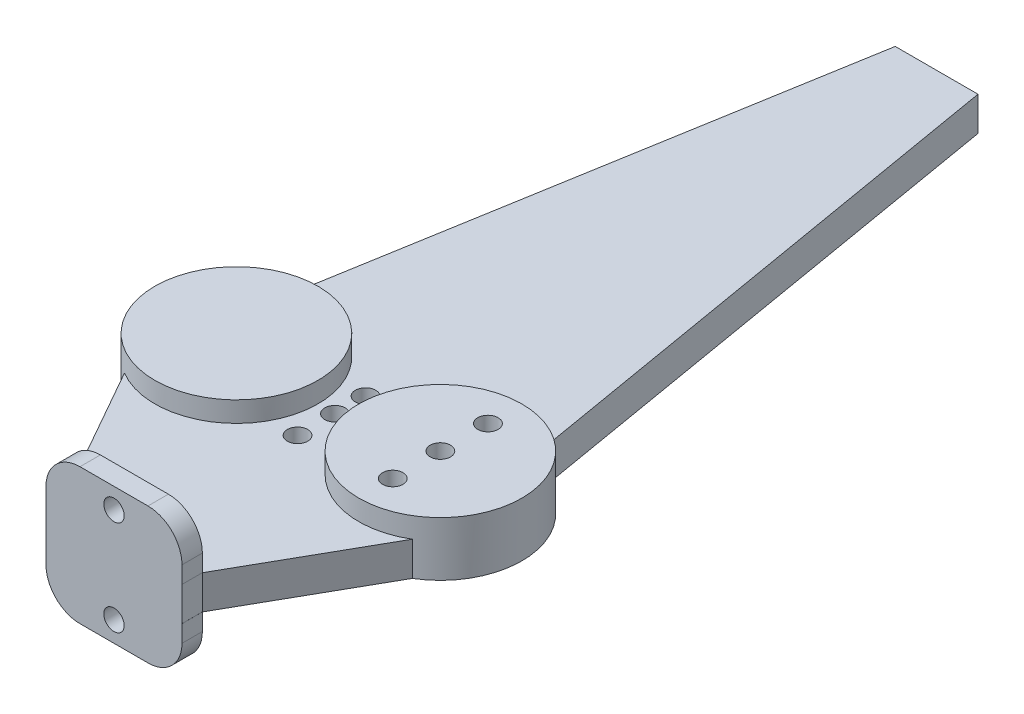
SolidWorks part; units mm, degrees
ref_plane "Front Plane" through (0, 0, 0) normal (0, 0, 1) x (1, 0, 0)
ref_plane "Top Plane" through (0, 0, 0) normal (0, 1, 0) x (1, 0, 0)
ref_plane "Right Plane" through (0, 0, 0) normal (1, 0, 0) x (0, 0, -1)
sketch "Sketch1" plane through (0, 0, 0) normal (0, 1, 0) x (1, 0, 0)
  line L0 (-10, -44) -> (10, -44)
  line L1 (-6.0865, 59) -> (6.0865, 59)
  line L3 (-10, -59) -> (10, -59)
  line L6 (-19.4049, -42.4032) -> (-18.521, -40.4718) construction
  line L7 (-10, -44) -> (-10, -59)
  line L8 (10, -44) -> (10, -59)
  line L9 (-10, -59) -> (10, -59)
  line L12 (0, 23.2923) -> (-7.3391, -19.7636)
  line L16 (-21.1665, -39.2944) -> (-10, -59)
  line L17 (-7.9884, -19.2616) -> (-7.7512, -16.9378) construction
  line L21 (0, 23.2923) -> (7.3391, -19.7636)
  line L22 (21.1665, -39.2944) -> (10, -59)
  line L23 (18.521, -40.4718) -> (19.4049, -42.4032) construction
  line L24 (6.0865, 59) -> (19.1685, -17.7473)
  line L25 (-8.6201, -18.8365) -> (-6.3269, -13.8254) construction
  line L26 (6.3269, -13.8254) -> (8.6201, -18.8365) construction
  line L28 (7.7512, -16.9378) -> (7.9884, -19.2616) construction
  line L29 (-6.0865, 59) -> (-19.1685, -17.7473)
  circle A0 centre (15, -29) radius 12
  circle A1 centre (-15, -29) radius 12
  point P0 (0, 0)
  point P6 (-15, -29)
  point P7 (0, -51.5)
  point P8 (15, -29)
  point P16 (0, 59)
  point P17 (0, 59)
  dimension "D3" = 20
  dimension "D4" = 15
  dimension "D5" = 30
  dimension "D6" = 30
extrude "Boss-Extrude1" add sketch "Sketch1" along normal blind 5 contours A1 L12 L21 A0 L24 L1 L29 | A1 L16 L7 L0 L8 L22 A0 L21 L12 | A0 | A1 | L8 L0 L7 L3
sketch "Sketch2" plane through (0, 5, 0) normal (0, 1, 0) x (1, 0, 0)
  circle A0 centre (15, -29) radius 12
  circle A1 centre (-15, -29) radius 12
extrude "Boss-Extrude2" add sketch "Sketch2" along normal blind 3
sketch "Sketch3" plane through (0, 0, 59) normal (0, 0, 1) x (1, 0, 0)
  line L0 (-10, 5) -> (-10, 0)
  line L6 (-10.0072, 12.5) -> (9.9928, 12.5)
  line L9 (9.9855, 5) -> (9.9855, 0)
  line L10 (-10, 5) -> (-10, 0) construction
  line L13 (-10.0072, 12.5) -> (-10.0072, -7.5)
  line L14 (-10.0072, -7.5) -> (9.9928, -7.5)
  line L15 (9.9928, 12.5) -> (9.9928, -7.5)
  point P0 (-0.0072, 2.5)
  point P13 (-0.0072, 5)
  point P14 (9.9855, 2.5)
  point P15 (-0.0072, 2.5)
  point P17 (-0.0072, 2.5)
  line M9 (-10, 0) -> (10, 0)
  line M11 (10, 5) -> (-10, 5)
  line M12 (-10, 5) -> (-10, 0)
  dimension "D1" = 20
  dimension "D2" = 20
  dimension "D4" = 9.9928
extrude "Boss-Extrude12" add sketch "Sketch3" along normal blind 3 separate body contours L15 L6 L13 L14 M9 M12 M11 | L9 M11 M12 M9
fillet "Fillet1" radius 5 4 edges at (9.9928, -7.5, 60.5) (-10.0072, -7.5, 60.5) (9.9928, 12.5, 60.5) (-10.0072, 12.5, 60.5)
hole_wizard "Ø3.0mm Dowel Hole1" positions "Sketch5" profile "Sketch7" hole size "Ø3.0" standard "ISO"
sketch "Sketch5" plane through (0, 0, 59) normal (0, 0, -1) x (-1, 0, 0)
  line L0 (-9.9928, 7.5) -> (-9.9928, 5) construction
  line L1 (5.0072, 12.5) -> (-4.9928, 12.5) construction
  point P0 (0.0072, 9.5)
  point P3 (0.0072, -4.5)
  dimension "D1" = 10
  dimension "D2" = 14
  dimension "D3" = 3
sketch "Sketch7" plane through (-0.0072, 9.5, 59) normal (1, 0, 0) x (0, 1, 0)
  line L0 (0, 0) -> (0, 29.9013)
  line L1 (0, 29.9013) -> (1.5, 29)
  line L2 (1.5, 29) -> (1.5, 0)
  line L5 (1.5, 0) -> (0, 0)
  line L10 (0, 29.9013) -> (-1.5, 29) construction
  line L11 (0, -6.35) -> (0, 107.95) construction
  dimension "Hole Dia." = 3
  dimension "Hole Depth" = 29
  dimension "Drill Angle" = 118
hole_wizard "Ø3.0mm Dowel Hole2" positions "Sketch8" profile "Sketch9" hole size "Ø3.0" standard "ISO"
sketch "Sketch8" plane through (0, 8, 0) normal (0, 1, 0) x (1, 0, 0)
  point P0 (15, -29)
  point P3 (15, -22)
  point P5 (15, -36)
  point P10 (-0.5015, -29)
  point P11 (-0.5015, -34.5051)
  point P13 (-0.5015, -24.5051)
  dimension "D1" = 7
  dimension "D2" = 7
  dimension "D3" = 16.14
  dimension "D4" = 10
  dimension "D6" = 16.45
sketch "Sketch9" plane through (15, 8, 29) normal (1, 0, 0) x (0, 0, 1)
  line L0 (0, 0) -> (0, 29.9013)
  line L1 (0, 29.9013) -> (1.5, 29)
  line L2 (1.5, 29) -> (1.5, 0)
  line L5 (1.5, 0) -> (0, 0)
  line L10 (0, 29.9013) -> (-1.5, 29) construction
  line L11 (0, -6.35) -> (0, 107.95) construction
  dimension "Hole Dia." = 3
  dimension "Hole Depth" = 29
  dimension "Drill Angle" = 118
